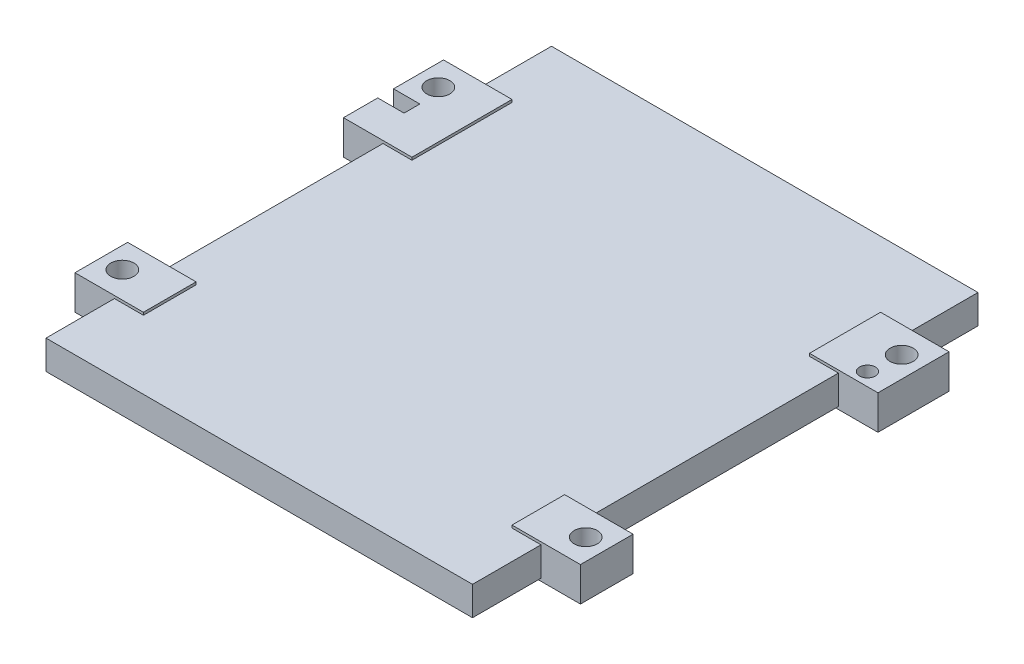
SolidWorks part; units mm, degrees
ref_plane "Спереди" through (0, 0, 0) normal (0, 0, 1) x (1, 0, 0)
ref_plane "Сверху" through (0, 0, 0) normal (0, 1, 0) x (1, 0, 0)
ref_plane "Справа" through (0, 0, 0) normal (1, 0, 0) x (0, 0, -1)
sketch "Эскиз1" plane through (0, 0, 0) normal (0, 1, 0) x (1, 0, 0)
  line L0 (-40.5, 30) -> (40.5, 30) construction
  line L1 (40.5, -48) -> (-40.5, -48)
  line L2 (40.5, -48) -> (40.5, 48)
  line L3 (40.5, 48) -> (-40.5, 48)
  line L4 (-40.5, -48) -> (-40.5, 48)
  line L5 (40.5, -48) -> (-40.5, 48) construction
  line L6 (40.5, 48) -> (-40.5, -48) construction
  line L7 (-40.5, 24) -> (49959.5, 24) construction
  line L8 (0, 0) -> (0, 50000) construction
  line L9 (0, 0) -> (50000, 0) construction
  line L10 (-48, -69.2869) -> (-48, 49930.7131) construction
  line L11 (48, -69.5127) -> (48, 49930.4873) construction
  line L12 (0, -30) -> (50000, -30) construction
  line L13 (0, -35) -> (50000, -35) construction
  line L14 (0, -25) -> (50000, -25) construction
  line L15 (0, 35) -> (50000, 35) construction
  line L16 (0, 16) -> (50000, 16) construction
  line L17 (0, 21.5) -> (50000, 21.5) construction
  line L18 (35, -48) -> (35, 49952) construction
  line L19 (-35, -48) -> (-35, 49952) construction
  line L20 (44, 35) -> (44, -49965) construction
  line L21 (48, -25) -> (35, -25)
  line L22 (48, -25) -> (48, -35)
  line L23 (48, -35) -> (35, -35)
  line L24 (35, -25) -> (35, -35)
  line L25 (-35, -35) -> (-48, -35)
  line L26 (-35, -35) -> (-35, -25)
  line L27 (-35, -25) -> (-48, -25)
  line L28 (-48, -35) -> (-48, -25)
  line L29 (48, 35) -> (35, 35)
  line L30 (48, 35) -> (48, 21.5)
  line L31 (48, 21.5) -> (35, 21.5)
  line L32 (35, 35) -> (35, 21.5)
  line L33 (-35, 35) -> (-48, 35)
  line L34 (-35, 35) -> (-35, 16)
  line L35 (-35, 16) -> (-48, 16)
  line L36 (-48, 35) -> (-48, 16)
  line L37 (-44, 35) -> (-44, -49965) construction
  line L38 (43.5, 16) -> (43.5, 50016) construction
  circle A0 centre (44, -30) radius 2.2
  circle A1 centre (-44, -30) radius 2.2
  circle A2 centre (44, 30) radius 2.2
  circle A3 centre (-44, 30) radius 2.2
  circle A4 centre (43.5, 24) radius 1.5
  point P0 (0, 0)
  dimension "D17" = 4.4
  dimension "D18" = 4.4
  dimension "D19" = 4.4
  dimension "D20" = 4.4
  dimension "D22" = 3
  dimension "D1" = 96
  dimension "D2" = 81
  dimension "D3" = 18
  dimension "D4" = 24
  dimension "D5" = 48
  dimension "D6" = 48
  dimension "D7" = 60
  dimension "D8" = 5
  dimension "D9" = 5
  dimension "D10" = 5
  dimension "D11" = 19
  dimension "D12" = 13.5
  dimension "D13" = 13
  dimension "D14" = 13
  dimension "D15" = 4
  dimension "D16" = 88
  dimension "D21" = 4.5
sketch "Эскиз4" plane through (0, 0, 0) normal (0, 1, 0) x (1, 0, 0)
  line L0 (-40.5, 30) -> (40.5, 30) construction
  line L1 (40.5, -48) -> (-40.5, -48)
  line L2 (40.5, -48) -> (40.5, 48)
  line L3 (40.5, 48) -> (-40.5, 48)
  line L4 (-40.5, -48) -> (-40.5, 48)
  line L5 (40.5, -48) -> (-40.5, 48) construction
  line L6 (40.5, 48) -> (-40.5, -48) construction
  line L7 (-40.5, 24) -> (49959.5, 24) construction
  line L8 (0, 0) -> (0, 50000) construction
  line L9 (0, 0) -> (50000, 0) construction
  line L10 (-48, -69.2869) -> (-48, 49930.7131) construction
  line L11 (48, -69.5127) -> (48, 49930.4873) construction
  line L12 (0, -30) -> (50000, -30) construction
  line L13 (0, -35) -> (50000, -35) construction
  line L14 (0, -25) -> (50000, -25) construction
  line L15 (0, 35) -> (50000, 35) construction
  line L16 (0, 16) -> (50000, 16) construction
  line L17 (0, 21.5) -> (50000, 21.5) construction
  line L18 (35, -48) -> (35, 49952) construction
  line L19 (-35, -48) -> (-35, 49952) construction
  line L20 (44, 35) -> (44, -49965) construction
  line L21 (48, -25) -> (35, -25)
  line L22 (48, -25) -> (48, -35)
  line L23 (48, -35) -> (35, -35)
  line L24 (35, -25) -> (35, -35)
  line L25 (-35, -35) -> (-48, -35)
  line L26 (-35, -35) -> (-35, -25)
  line L27 (-35, -25) -> (-48, -25)
  line L28 (-48, -35) -> (-48, -25)
  line L29 (48, 35) -> (35, 35)
  line L30 (48, 35) -> (48, 21.5)
  line L31 (48, 21.5) -> (35, 21.5)
  line L32 (35, 35) -> (35, 21.5)
  line L33 (-35, 35) -> (-48, 35)
  line L34 (-35, 35) -> (-35, 16)
  line L35 (-35, 16) -> (-48, 16)
  line L36 (-48, 35) -> (-48, 16)
  line L37 (-44, 35) -> (-44, -49965) construction
  line L38 (43.5, 16) -> (43.5, 50016) construction
  circle A0 centre (44, -30) radius 2.2
  circle A1 centre (-44, -30) radius 2.2
  circle A2 centre (44, 30) radius 2.2
  circle A3 centre (-44, 30) radius 2.2
  circle A4 centre (43.5, 24) radius 1.5
  point P0 (0, 0)
  dimension "D17" = 4.4
  dimension "D18" = 4.4
  dimension "D19" = 4.4
  dimension "D20" = 4.4
  dimension "D22" = 3
  dimension "D1" = 96
  dimension "D2" = 81
  dimension "D3" = 18
  dimension "D4" = 24
  dimension "D5" = 48
  dimension "D6" = 48
  dimension "D7" = 60
  dimension "D8" = 5
  dimension "D9" = 5
  dimension "D10" = 5
  dimension "D11" = 19
  dimension "D12" = 13.5
  dimension "D13" = 13
  dimension "D14" = 13
  dimension "D15" = 4
  dimension "D16" = 88
  dimension "D21" = 4.5
sketch "Эскиз5" plane through (0, 0, 0) normal (0, 1, 0) x (1, 0, 0)
  line L0 (-40.5, 30) -> (40.5, 30) construction
  line L1 (40.5, -48) -> (-40.5, -48)
  line L2 (40.5, -48) -> (40.5, 48)
  line L3 (40.5, 48) -> (-40.5, 48)
  line L4 (-40.5, -48) -> (-40.5, 48)
  line L5 (40.5, -48) -> (-40.5, 48) construction
  line L6 (40.5, 48) -> (-40.5, -48) construction
  line L7 (-40.5, 24) -> (49959.5, 24) construction
  line L8 (0, 0) -> (0, 50000) construction
  line L9 (0, 0) -> (50000, 0) construction
  line L10 (-48, -69.2869) -> (-48, 49930.7131) construction
  line L11 (48, -69.5127) -> (48, 49930.4873) construction
  line L12 (0, -30) -> (50000, -30) construction
  line L13 (0, -35) -> (50000, -35) construction
  line L14 (0, -25) -> (50000, -25) construction
  line L15 (0, 35) -> (50000, 35) construction
  line L16 (0, 16) -> (50000, 16) construction
  line L17 (0, 21.5) -> (50000, 21.5) construction
  line L18 (35, -48) -> (35, 49952) construction
  line L19 (-35, -48) -> (-35, 49952) construction
  line L20 (44, 35) -> (44, -49965) construction
  line L21 (48, -25) -> (35, -25)
  line L22 (48, -25) -> (48, -35)
  line L23 (48, -35) -> (35, -35)
  line L24 (35, -25) -> (35, -35)
  line L25 (-35, -35) -> (-48, -35)
  line L26 (-35, -35) -> (-35, -25)
  line L27 (-35, -25) -> (-48, -25)
  line L28 (-48, -35) -> (-48, -25)
  line L29 (48, 35) -> (35, 35)
  line L30 (48, 35) -> (48, 21.5)
  line L31 (48, 21.5) -> (35, 21.5)
  line L32 (35, 35) -> (35, 21.5)
  line L33 (-35, 35) -> (-48, 35)
  line L34 (-35, 35) -> (-35, 16)
  line L35 (-35, 16) -> (-48, 16)
  line L36 (-48, 35) -> (-48, 16)
  line L37 (-44, 35) -> (-44, -49965) construction
  line L38 (43.5, 16) -> (43.5, 50016) construction
  line L39 (-48, 22.5) -> (-43, 22.5)
  line L40 (-43, 22.5) -> (-43, 25.5)
  line L41 (-43, 25.5) -> (-48, 25.5)
  circle A0 centre (44, -30) radius 2.2
  circle A1 centre (-44, -30) radius 2.2
  circle A2 centre (44, 30) radius 2.2
  circle A3 centre (-44, 30) radius 2.2
  circle A4 centre (43.5, 24) radius 1.5
  point P0 (0, 0)
  dimension "D17" = 4.4
  dimension "D18" = 4.4
  dimension "D19" = 4.4
  dimension "D20" = 4.4
  dimension "D22" = 3
  dimension "D1" = 96
  dimension "D2" = 81
  dimension "D3" = 18
  dimension "D4" = 24
  dimension "D5" = 48
  dimension "D6" = 48
  dimension "D7" = 60
  dimension "D8" = 5
  dimension "D9" = 5
  dimension "D10" = 5
  dimension "D11" = 19
  dimension "D12" = 13.5
  dimension "D13" = 13
  dimension "D14" = 13
  dimension "D15" = 4
  dimension "D16" = 88
  dimension "D21" = 4.5
  dimension "D23" = 5
  dimension "D24" = 1.5
  dimension "D25" = 1.5
extrude "Бобышка-Вытянуть3" add sketch "Эскиз4" along normal blind 5.5 contours L34 L35 L4 L27 L26 L25 L1 L2 L23 L24 L21 L31 L32 L29 L3 L33
extrude "Бобышка-Вытянуть4" add sketch "Эскиз5" along normal blind 6 and the other way blind 0.5 contours L21 L24 L23 L2 | L23 L22 L21 L2 A0 | L29 L32 L31 L2 | L31 L30 L29 L2 A4 A2 | L35 L34 L33 L4 | L33 L36 L35 L4 A3 | L26 L27 L4 L25 | L28 L25 L4 L27 A1
